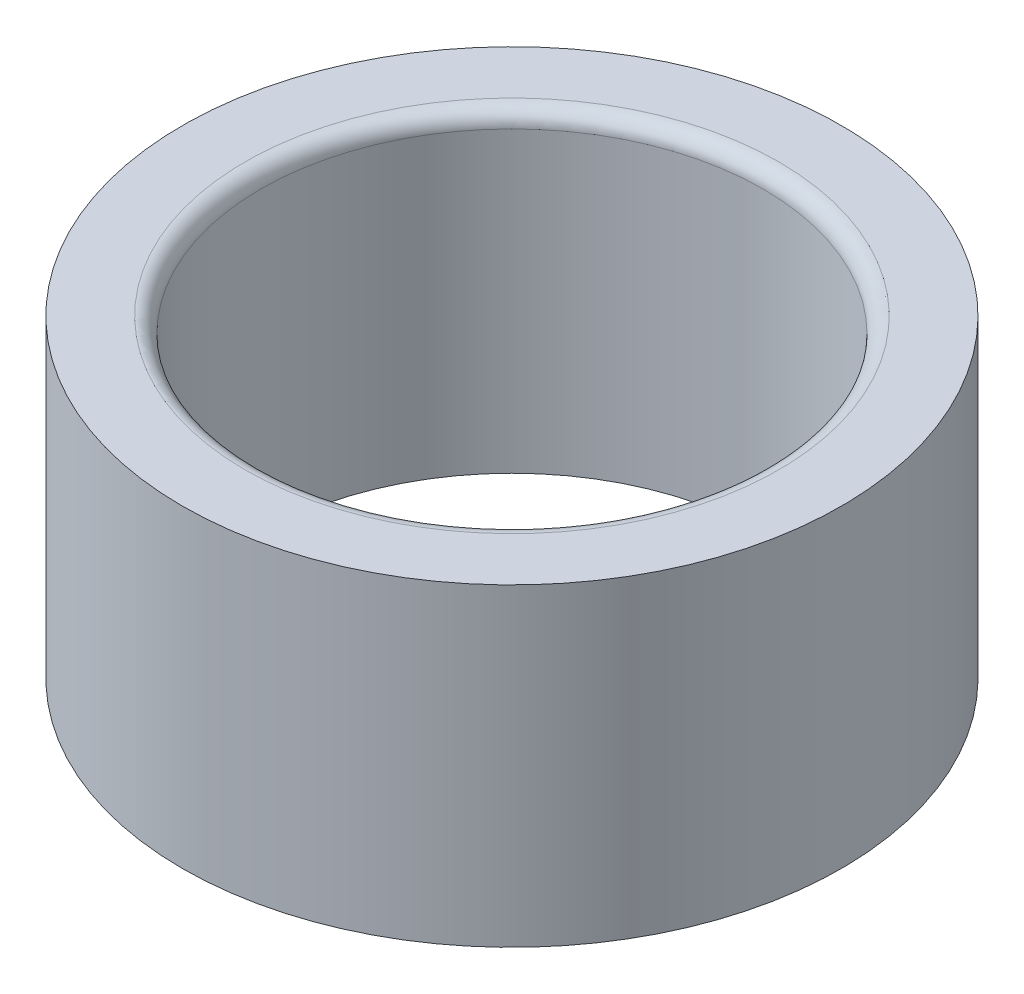
SolidWorks part; units mm, degrees
ref_plane "Front Plane" through (0, 0, 0) normal (0, 0, 1) x (1, 0, 0)
ref_plane "Top Plane" through (0, 0, 0) normal (0, 1, 0) x (1, 0, 0)
ref_plane "Right Plane" through (0, 0, 0) normal (1, 0, 0) x (0, 0, -1)
sketch "Sketch1" plane through (0, 0, 0) normal (0, 1, 0) x (1, 0, 0)
  circle A0 centre (0, 0) radius 16
  circle A1 centre (0, 0) radius 21
  dimension "D1" = 32
  dimension "D2" = 5
extrude "Boss-Extrude1" add sketch "Sketch1" along normal blind 20
fillet "Fillet1" radius 1 1 edges at (0, 20, 16)
